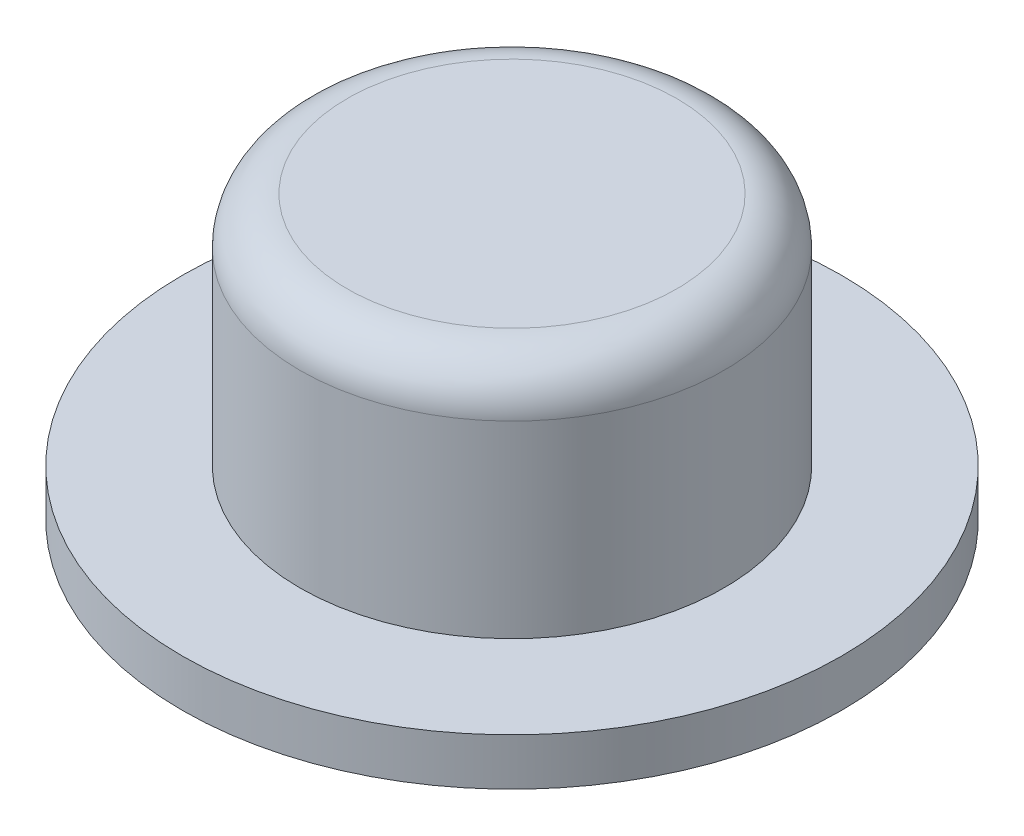
SolidWorks part; units mm, degrees
ref_plane "Front Plane" through (0, 0, 0) normal (0, 0, 1) x (1, 0, 0)
ref_plane "Top Plane" through (0, 0, 0) normal (0, 1, 0) x (1, 0, 0)
ref_plane "Right Plane" through (0, 0, 0) normal (1, 0, 0) x (0, 0, -1)
sketch "Sketch1" plane through (0, 0, 0) normal (0, 0, 1) x (1, 0, 0)
  line L0 (0, 0) -> (0, 6)
  line L1 (0, 6) -> (-3.5, 6)
  line L2 (-4.5, 5) -> (-4.5, 1)
  line L3 (-4.5, 1) -> (-7, 1)
  line L4 (-7, 1) -> (-7, 0)
  line L5 (-7, 0) -> (0, 0)
  arc A0 (-3.5, 6) -> (-4.5, 5) centre (-3.5, 5) ccw
  point P9 (-4.5, 6)
  dimension "D5" = 1
  dimension "D1" = 6
  dimension "D2" = 4.5
  dimension "D3" = 7
  dimension "D4" = 1
revolve "Revolve1" add sketch "Sketch1" angle 360 about L0
